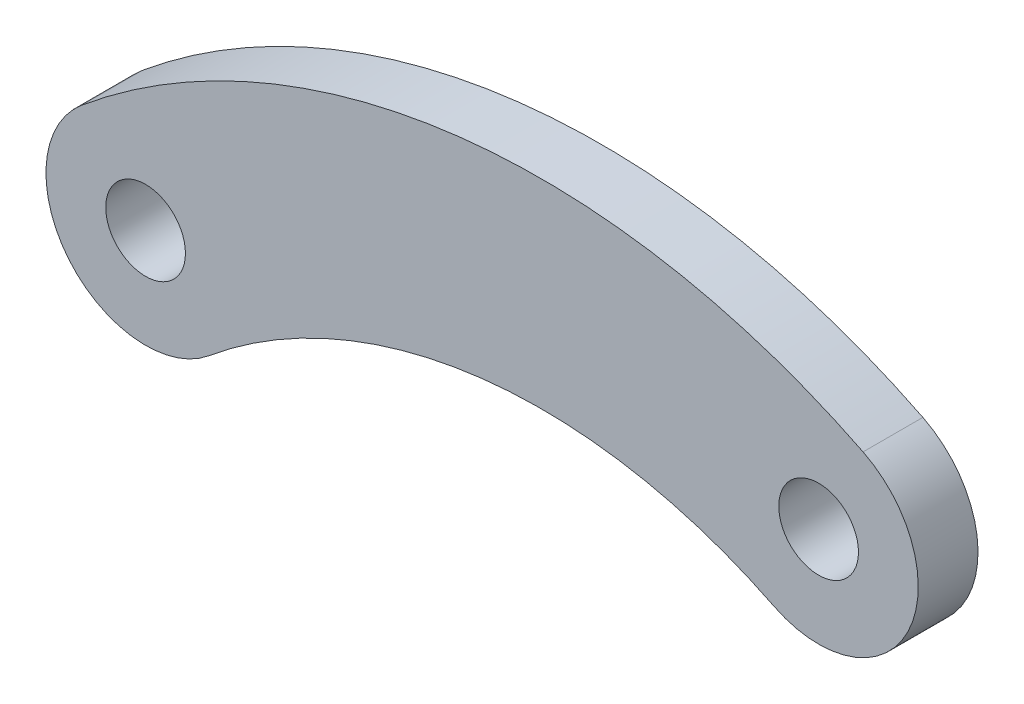
SolidWorks part; units mm, degrees
ref_plane "Front Plane" through (0, 0, 0) normal (0, 0, 1) x (1, 0, 0)
ref_plane "Top Plane" through (0, 0, 0) normal (0, 1, 0) x (1, 0, 0)
ref_plane "Right Plane" through (0, 0, 0) normal (1, 0, 0) x (0, 0, -1)
sketch "Sketch1" plane through (0, 0, 0) normal (0, 0, 1) x (1, 0, 0)
  arc A0 (0, 0) -> (16.8876, 1.9512) centre (9.9401, -11.9739) cw construction
  arc A1 (18.0038, 4.1883) -> (-1.5968, 1.9236) centre (9.9401, -11.9739) ccw
  arc A2 (15.7715, -0.2858) -> (1.5968, -1.9236) centre (9.9401, -11.9739) ccw
  arc A3 (15.7715, -0.2858) -> (18.0038, 4.1883) centre (16.8876, 1.9512) ccw
  arc A4 (-1.5968, 1.9236) -> (1.5968, -1.9236) centre (0, 0) ccw
  circle A5 centre (0, 0) radius 1
  circle A6 centre (16.8876, 1.9512) radius 1
  point P3 (8.1538, 3.4853)
  dimension "D2" = 2.5
  dimension "D3" = 2
  dimension "D4" = 2
  dimension "D5" = 15.5621
  dimension "D6" = 4.1883
  dimension "D1" = 17
extrude "Boss-Extrude1" add sketch "Sketch1" along normal blind 1.5
